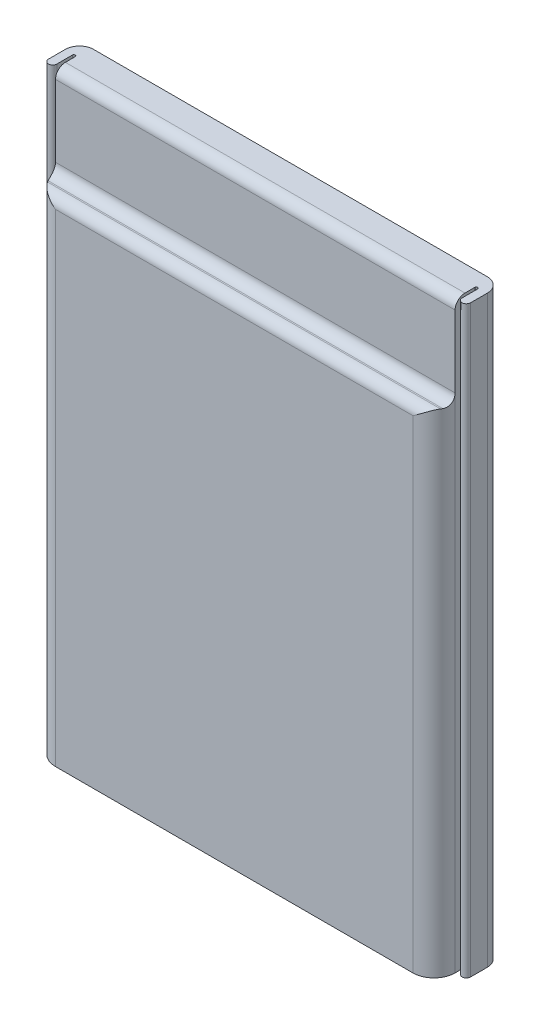
SolidWorks part; units mm, degrees
ref_plane "Front" through (0, 0, 0) normal (0, 0, 1) x (1, 0, 0)
ref_plane "Top" through (0, 0, 0) normal (0, 1, 0) x (1, 0, 0)
ref_plane "Right" through (0, 0, 0) normal (1, 0, 0) x (0, 0, -1)
sketch "Эскиз1" plane through (0, 0, 0) normal (0, 1, 0) x (1, 0, 0)
  line L0 (-14, 0) -> (14, 0)
  line L1 (-12.7, -4) -> (12.7, -4)
  line L2 (-15, -1) -> (-15, -2.2)
  line L3 (15, -1) -> (15, -2.2)
  line L4 (-14.2, -2.5) -> (-14.2, -1.1)
  line L5 (14.2, -1.1) -> (14.2, -2.5)
  line L6 (14.4, -2.2) -> (14.4, -1.1)
  line L7 (-14.4, -2.2) -> (-14.4, -1.1)
  arc A0 (-14, 0) -> (-15, -1) centre (-14, -1) ccw
  arc A1 (14, 0) -> (15, -1) centre (14, -1) cw
  arc A2 (-14.2, -2.5) -> (-12.7, -4) centre (-12.7, -2.5) ccw
  arc A3 (14.2, -2.5) -> (12.7, -4) centre (12.7, -2.5) cw
  arc A4 (15, -2.2) -> (14.4, -2.2) centre (14.7, -2.2) cw
  arc A5 (14.2, -1.1) -> (14.4, -1.1) centre (14.3, -1.1) cw
  arc A6 (-15, -2.2) -> (-14.4, -2.2) centre (-14.7, -2.2) ccw
  arc A7 (-14.2, -1.1) -> (-14.4, -1.1) centre (-14.3, -1.1) ccw
  point P20 (14.3, -1)
  point P21 (14.7, -2.5)
  point P27 (-14.3, -1)
  point P28 (-14.7, -2.5)
  dimension "D1" = 30
  dimension "D3" = 1.5
  dimension "D4" = 1
  dimension "D5" = 0.3
  dimension "D6" = 0.1
  dimension "D2" = 4
extrude "Бобышка-Вытянуть1" add sketch "Эскиз1" along normal mid plane 41.5
sketch "Эскиз2" plane through (0, 0, 0) normal (1, 0, 0) x (0, 0, -1)
  line L0 (-2.5, 20.05) -> (-2.5, 14.95)
  line L1 (-3.2, 14.25) -> (-3.3, 14.25)
  line L2 (-4, 20.75) -> (-4, 13.55)
  line L3 (-4, 20.75) -> (-4, -20.75) construction
  line L6 (-4, 20.75) -> (-1.8, 20.75)
  line L7 (0, 20.75) -> (-1, 20.75) construction
  arc A0 (-2.5, 14.95) -> (-3.2, 14.25) centre (-3.2, 14.95) cw
  arc A1 (-3.3, 14.25) -> (-4, 13.55) centre (-3.3, 13.55) ccw
  arc A2 (-1.8, 20.75) -> (-2.5, 20.05) centre (-1.8, 20.05) ccw
  dimension "D1" = 0.7
  dimension "D2" = 2.5
  dimension "D3" = 6.5
extrude "Вырез-Вытянуть1" cut sketch "Эскиз2" against normal up to next and the other way up to next
